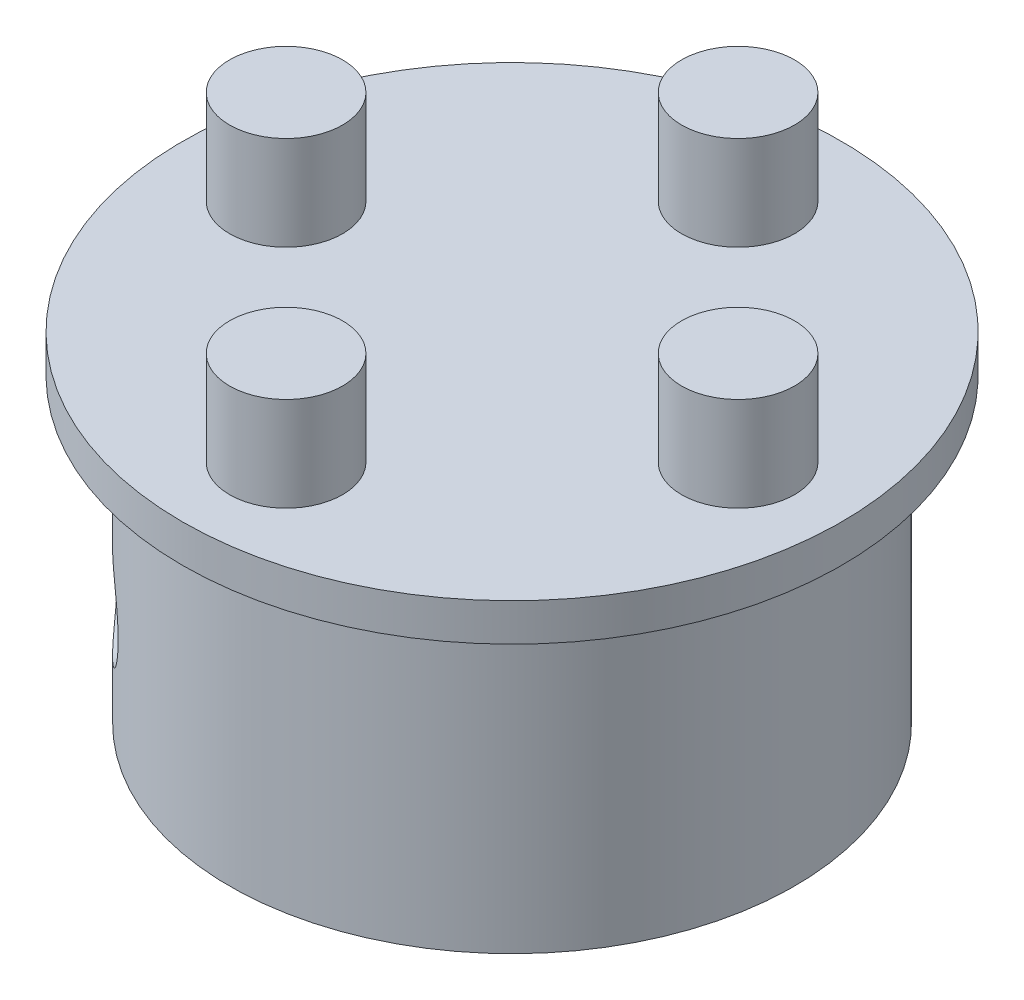
SolidWorks part; units mm, degrees
ref_plane "Front Plane" through (0, 0, 0) normal (0, 0, 1) x (1, 0, 0)
ref_plane "Top Plane" through (0, 0, 0) normal (0, 1, 0) x (1, 0, 0)
ref_plane "Right Plane" through (0, 0, 0) normal (1, 0, 0) x (0, 0, -1)
sketch "Sketch1" plane through (0, 0, 0) normal (0, 1, 0) x (1, 0, 0)
  circle A0 centre (0, 0) radius 17.5
  dimension "D1" = 35
extrude "Boss-Extrude1" add sketch "Sketch1" along normal blind 2
sketch "Sketch2" plane through (0, 2, 0) normal (0, 1, 0) x (1, 0, 0)
  line L0 (-17.5, 0) -> (-5.2, 0) construction
  line L1 (-5.2, 0) -> (5.2, 0) construction
  line L2 (5.2, 0) -> (17.5, 0) construction
  circle A0 centre (0, 0) radius 17.5 construction
  arc A1 (-5.2, 0) -> (5.2, 0) centre (0, 0) ccw construction
  circle A2 centre (12, 0) radius 6.8 construction
  arc A3 (5.2, 0) -> (-5.2, 0) centre (0, 0) ccw construction
  circle A4 centre (12, 0) radius 3
  arc A5 (11.625, 2.9765) -> (10.0733, 6.5213) centre (0, 0) ccw construction
  arc A6 (10.0733, 6.5213) -> (-12, 0) centre (0, 0) ccw construction
  arc A7 (-12, 0) -> (10.0733, -6.5213) centre (0, 0) ccw construction
  arc A8 (10.0733, -6.5213) -> (11.625, -2.9765) centre (0, 0) ccw construction
  arc A9 (11.625, -2.9765) -> (12, 0) centre (0, 0) ccw construction
  arc A10 (12, 0) -> (11.625, 2.9765) centre (0, 0) ccw construction
  circle A11 centre (0, -12) radius 3
  circle A12 centre (-12, 0) radius 3
  circle A13 centre (0, 12) radius 3
  point P26 (0, 0)
  dimension "D1" = 10.4
  dimension "D2" = 13.6
  dimension "D3" = 6
  dimension "D4" = 4
extrude "Boss-Extrude2" add sketch "Sketch2" along normal blind 5
sketch "Sketch3" plane through (0, 0, 0) normal (0, -1, 0) x (1, 0, 0)
  circle A0 centre (0, 0) radius 15
  dimension "D1" = 30
extrude "Boss-Extrude3" add sketch "Sketch3" along normal blind 16
sketch "Sketch4" plane through (0, -16, 0) normal (0, -1, 0) x (1, 0, 0)
  circle A0 centre (0, 0) radius 10 construction
  circle A1 centre (-10, 0) radius 2
  circle A2 centre (0, 10) radius 2
  circle A3 centre (10, 0) radius 2
  circle A4 centre (0, -10) radius 2
  point P14 (0, 0)
  dimension "D1" = 20
  dimension "D2" = 4
  dimension "D3" = 4
extrude "Cut-Extrude1" cut sketch "Sketch4" against normal blind 5
ref_plane "Plane1" through (-8.1213, 0, 8.1213) normal (-0.7071, 0, 0.7071) x (0.7071, 0, 0.7071)
sketch "Sketch5" plane through (-8.1213, 0, 8.1213) normal (-0.7071, 0, 0.7071) x (0.7071, 0, 0.7071)
  circle A0 centre (0, -10.423) radius 2.5
  dimension "D1" = 5
extrude "Cut-Extrude2" cut sketch "Sketch5" along normal blind 10 contours A0
